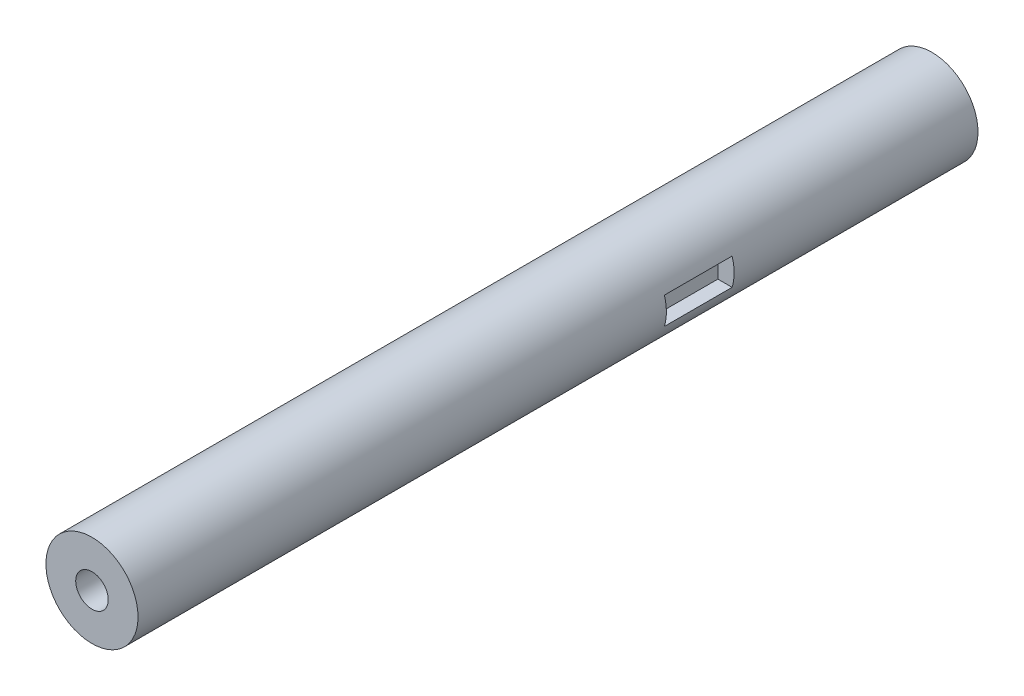
SolidWorks part; units mm, degrees
ref_plane "Спереди" through (0, 0, 0) normal (0, 0, 1) x (1, 0, 0)
ref_plane "Сверху" through (0, 0, 0) normal (0, 1, 0) x (1, 0, 0)
ref_plane "Справа" through (0, 0, 0) normal (1, 0, 0) x (0, 0, -1)
sketch "Эскиз1" plane through (0, 0, 0) normal (0, 0, 1) x (1, 0, 0)
  circle A0 centre (0, 0) radius 8.5
  circle A1 centre (0, 0) radius 3
extrude "Axle_envelope" add sketch "Эскиз1" along normal blind 155 from offset 75
sketch "Эскиз2" plane through (0, 0, 0) normal (0, 0, 1) x (1, 0, 0)
  line L0 (5.5, -2.5) -> (10.5, -2.5)
  line L1 (10.5, -2.5) -> (10.5, 2.5)
  line L2 (10.5, 2.5) -> (5.5, 2.5)
  line L3 (5.5, 2.5) -> (5.5, -2.5)
extrude "Axle_keyway" cut sketch "Эскиз2" along normal blind 12.5 from offset 30
